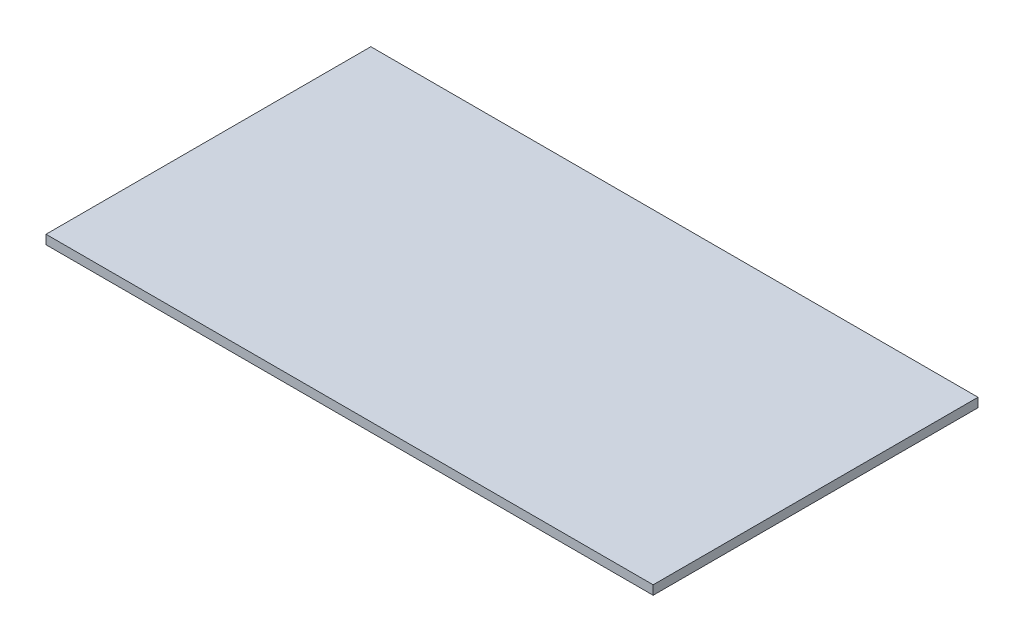
SolidWorks part; units mm, degrees
material "Balsa"
ref_plane "Front Plane" through (0, 0, 0) normal (0, 0, 1) x (1, 0, 0)
ref_plane "Top Plane" through (0, 0, 0) normal (0, 1, 0) x (1, 0, 0)
ref_plane "Right Plane" through (0, 0, 0) normal (1, 0, 0) x (0, 0, -1)
sketch "Sketch1" plane through (0, 0, 0) normal (0, 1, 0) x (1, 0, 0)
  line L1 (-500, -267.5) -> (500, -267.5)
  line L2 (-500, -267.5) -> (-500, 267.5)
  line L3 (-500, 267.5) -> (500, 267.5)
  line L4 (500, -267.5) -> (500, 267.5)
  line L5 (-500, -267.5) -> (500, 267.5) construction
  line L6 (-500, 267.5) -> (500, -267.5) construction
  point P0 (0, 0)
  dimension "D1" = 1000
  dimension "D2" = 535
extrude "Boss-Extrude1" add sketch "Sketch1" along normal blind 15
